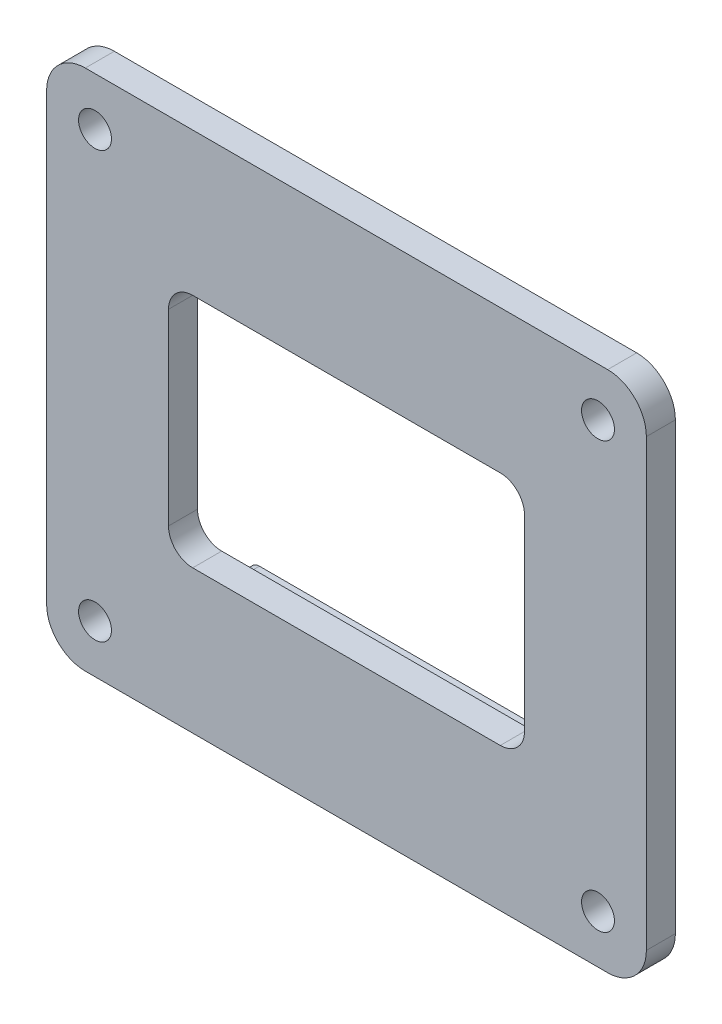
SolidWorks part; units mm, degrees
ref_plane "前视基准面" through (0, 0, 0) normal (0, 0, 1) x (1, 0, 0)
ref_plane "上视基准面" through (0, 0, 0) normal (0, 1, 0) x (1, 0, 0)
ref_plane "右视基准面" through (0, 0, 0) normal (1, 0, 0) x (0, 0, -1)
other "Configuration Table"
sketch "Outer_clamp_cover_62x54x3_Sketch" plane through (0, 0, 0) normal (0, 0, 1) x (1, 0, 0)
  line L0 (-27, -27) -> (27, -27)
  line L1 (31, -23) -> (31, 23)
  line L2 (27, 27) -> (-27, 27)
  line L3 (-31, 23) -> (-31, -23)
  line L4 (-15.9, -12.2) -> (15.9, -12.2)
  line L5 (18.4, -9.7) -> (18.4, 9.7)
  line L6 (15.9, 12.2) -> (-15.9, 12.2)
  line L7 (-18.4, 9.7) -> (-18.4, -9.7)
  arc A0 (27, -27) -> (31, -23) centre (27, -23) ccw
  arc A1 (31, 23) -> (27, 27) centre (27, 23) ccw
  arc A2 (-27, 27) -> (-31, 23) centre (-27, 23) ccw
  arc A3 (-31, -23) -> (-27, -27) centre (-27, -23) ccw
  circle A4 centre (-26, -22) radius 1.7
  circle A5 centre (-26, 22) radius 1.7
  circle A6 centre (26, -22) radius 1.7
  circle A7 centre (26, 22) radius 1.7
  arc A8 (15.9, -12.2) -> (18.4, -9.7) centre (15.9, -9.7) ccw
  arc A9 (18.4, 9.7) -> (15.9, 12.2) centre (15.9, 9.7) ccw
  arc A10 (-15.9, 12.2) -> (-18.4, 9.7) centre (-15.9, 9.7) ccw
  arc A11 (-18.4, -9.7) -> (-15.9, -12.2) centre (-15.9, -9.7) ccw
extrude "Outer_clamp_cover_62x54x3" add sketch "Outer_clamp_cover_62x54x3_Sketch" along normal blind 3 separate body
sketch "Two_case_retaining_feet_Sketch" plane through (0, 0, 0) normal (0, 0, 1) x (1, 0, 0)
  line L0 (-14, -17.5) -> (14, -17.5)
  line L1 (15, -16.5) -> (15, -14.6)
  line L2 (14, -13.6) -> (-14, -13.6)
  line L3 (-15, -14.6) -> (-15, -16.5)
  line L4 (-14, 13.6) -> (14, 13.6)
  line L5 (15, 14.6) -> (15, 16.5)
  line L6 (14, 17.5) -> (-14, 17.5)
  line L7 (-15, 16.5) -> (-15, 14.6)
  arc A0 (14, -17.5) -> (15, -16.5) centre (14, -16.5) ccw
  arc A1 (15, -14.6) -> (14, -13.6) centre (14, -14.6) ccw
  arc A2 (-14, -13.6) -> (-15, -14.6) centre (-14, -14.6) ccw
  arc A3 (-15, -16.5) -> (-14, -17.5) centre (-14, -16.5) ccw
  arc A4 (14, 13.6) -> (15, 14.6) centre (14, 14.6) ccw
  arc A5 (15, 16.5) -> (14, 17.5) centre (14, 16.5) ccw
  arc A6 (-14, 17.5) -> (-15, 16.5) centre (-14, 16.5) ccw
  arc A7 (-15, 14.6) -> (-14, 13.6) centre (-14, 14.6) ccw
extrude "Two_case_retaining_feet" add sketch "Two_case_retaining_feet_Sketch" along normal blind 2 from offset 2
